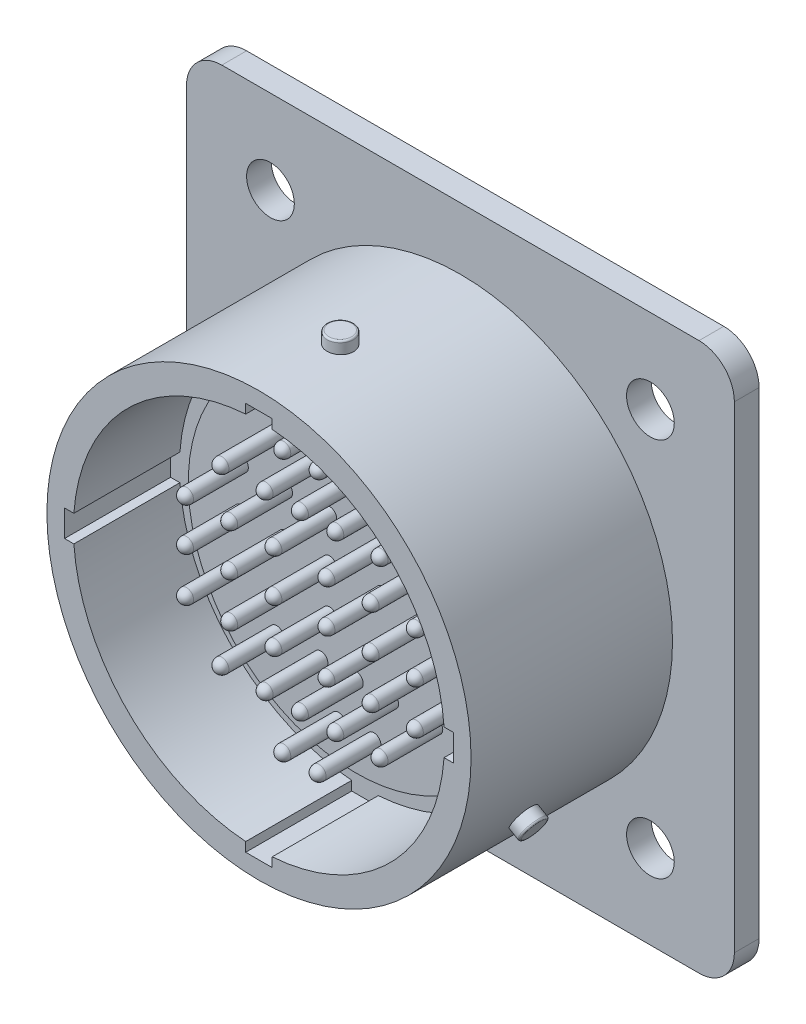
SolidWorks part; units mm, degrees
ref_plane "Спереди" through (0, 0, 0) normal (0, 0, 1) x (1, 0, 0)
ref_plane "Сверху" through (0, 0, 0) normal (0, 1, 0) x (1, 0, 0)
ref_plane "Справа" through (0, 0, 0) normal (1, 0, 0) x (0, 0, -1)
sketch "Эскиз1" plane through (0, 0, 0) normal (0, 0, 1) x (1, 0, 0)
  line L1 (-15.5, 15.5) -> (15.5, 15.5)
  line L2 (-15.5, 15.5) -> (-15.5, -15.5)
  line L3 (-15.5, -15.5) -> (15.5, -15.5)
  line L4 (15.5, 15.5) -> (15.5, -15.5)
  line L5 (0, -15.5) -> (0, 15.5) construction
  line L6 (-15.5, 0) -> (15.5, 0) construction
  point P0 (0, 0)
  dimension "D1" = 31
  dimension "D2" = 31
extrude "Бобышка-Вытянуть1" add sketch "Эскиз1" along normal mid plane 1.4
sketch "Эскиз2" plane through (0, 0, 0.7) normal (0, 0, 1) x (1, 0, 0)
  line L1 (-10.75, 10.75) -> (10.75, 10.75) construction
  line L2 (-10.75, 10.75) -> (-10.75, -10.75) construction
  line L3 (-10.75, -10.75) -> (10.75, -10.75) construction
  line L4 (10.75, 10.75) -> (10.75, -10.75) construction
  line L5 (0, -10.75) -> (0, 10.75) construction
  line L6 (-10.75, 0) -> (10.75, 0) construction
  circle A0 centre (-10.75, 10.75) radius 1.35
  circle A1 centre (10.75, 10.75) radius 1.35
  circle A2 centre (10.75, -10.75) radius 1.35
  circle A3 centre (-10.75, -10.75) radius 1.35
  point P0 (0, 0)
  dimension "D3" = 2.7
  dimension "D1" = 21.5
  dimension "D2" = 21.5
extrude "Вырез-Вытянуть1" cut sketch "Эскиз2" against normal blind 3.4
sketch "Эскиз4" plane through (0, 0, -0.7) normal (0, 0, -1) x (-1, 0, 0)
  circle A0 centre (0, 0) radius 11
  dimension "D1" = 22
extrude "Бобышка-Вытянуть2" add sketch "Эскиз4" along normal blind 1.6
sketch "Эскиз5" plane through (0, 0, 0.7) normal (0, 0, 1) x (1, 0, 0)
  circle A0 centre (0, 0) radius 12
  dimension "D1" = 24
extrude "Бобышка-Вытянуть3" add sketch "Эскиз5" along normal blind 11.4
sketch "Эскиз6" plane through (0, 0, -2.3) normal (0, 0, -1) x (-1, 0, 0)
  circle A2 centre (0, 0) radius 10
  circle A3 centre (0, 0) radius 10
  dimension "D1" = 1
fillet "Скругление1" radius 2 4 edges at (-15.5, -15.5, 0) (15.5, -15.5, 0) (-15.5, 15.5, 0) (15.5, 15.5, 0)
sketch "Эскиз11" plane through (0, 0, 12.1) normal (0, 0, 1) x (1, 0, 0)
  line L0 (0, 7.0707) -> (0, -7.5997) construction
  line L1 (-7.9185, 0) -> (8.5925, 0) construction
  line L2 (-0.75, 11) -> (0.75, 11)
  line L3 (-0.75, 11) -> (-0.75, 10.4732)
  line L4 (0.75, 11) -> (0.75, 10.4732)
  line L5 (11, 0.75) -> (10.4732, 0.75)
  line L6 (11, 0.75) -> (11, -0.75)
  line L7 (11, -0.75) -> (10.4732, -0.75)
  line L8 (0.75, -11) -> (0.75, -10.4732)
  line L9 (0.75, -11) -> (-0.75, -11)
  line L10 (-0.75, -11) -> (-0.75, -10.4732)
  line L11 (-11, -0.75) -> (-10.4732, -0.75)
  line L12 (-11, -0.75) -> (-11, 0.75)
  line L13 (-11, 0.75) -> (-10.4732, 0.75)
  arc A1 (-10.4732, -0.75) -> (-0.75, -10.4732) centre (0, 0) ccw
  circle A2 centre (0, 0) radius 10.5
  arc A3 (-0.75, 10.4732) -> (-10.4732, 0.75) centre (0, 0) ccw
  arc A4 (0.75, -10.4732) -> (10.4732, -0.75) centre (0, 0) ccw
  arc A5 (10.4732, 0.75) -> (0.75, 10.4732) centre (0, 0) ccw
  point P10 (0, 10.5)
  point P11 (0, 11)
  point P28 (0, 0)
  dimension "D2" = 0.5
  dimension "D3" = 1.5
  dimension "D1" = 1.5
  dimension "D4" = 4
extrude "Вырез-Вытянуть5" cut sketch "Эскиз11" against normal blind 6
sketch "Эскиз12" plane through (0, 0, 6.1) normal (0, 0, 1) x (1, 0, 0)
  circle A0 centre (0, 0) radius 9.5
  dimension "D1" = 19
extrude "Бобышка-Вытянуть5" add sketch "Эскиз12" along normal blind 0.5
sketch "Эскиз13" plane through (0, 0, 6.6) normal (0, 0, 1) x (1, 0, 0)
  line L0 (-6.7045, 0) -> (6.9732, 0) construction
  line L1 (0, 4.9143) -> (0, -4.8929) construction
  line L2 (-6.3605, 4.9143) -> (7.9732, 4.9143) construction
  line L3 (-6.3605, 7.4143) -> (7.9732, 7.4143) construction
  circle A4 centre (-1.5, 0) radius 0.4
  circle A6 centre (-4, 0) radius 0.4
  circle A7 centre (-6.5, 0) radius 0.4
  circle A8 centre (-1.5, -2.5) radius 0.4
  circle A9 centre (-4, -2.5) radius 0.4
  circle A10 centre (-6.5, -2.5) radius 0.4
  circle A11 centre (-4, 2.4143) radius 0.4
  circle A12 centre (-6.5, 2.4143) radius 0.4
  circle A13 centre (-1.5, 2.4143) radius 0.4
  circle A14 centre (0, 4.9143) radius 0.4
  circle A15 centre (-2, 4.9143) radius 0.4
  circle A16 centre (-4.5, 4.9143) radius 0.4
  circle A17 centre (-1, 7.4143) radius 0.4
  circle A18 centre (-2, -4.9143) radius 0.4
  circle A19 centre (-1, -7.4143) radius 0.4
  circle A20 centre (0, -4.9143) radius 0.4
  circle A21 centre (-4.5, -4.9143) radius 0.4
  circle A22 centre (4.5, -4.9143) radius 0.4
  circle A23 centre (1, -7.4143) radius 0.4
  circle A24 centre (2, -4.9143) radius 0.4
  circle A25 centre (1, 7.4143) radius 0.4
  circle A26 centre (4.5, 4.9143) radius 0.4
  circle A27 centre (2, 4.9143) radius 0.4
  circle A28 centre (1.5, 2.4143) radius 0.4
  circle A29 centre (6.5, 2.4143) radius 0.4
  circle A30 centre (4, 2.4143) radius 0.4
  circle A31 centre (6.5, -2.5) radius 0.4
  circle A32 centre (4, -2.5) radius 0.4
  circle A33 centre (1.5, -2.5) radius 0.4
  circle A34 centre (6.5, 0) radius 0.4
  circle A35 centre (4, 0) radius 0.4
  circle A36 centre (1.5, 0) radius 0.4
  dimension "D1" = 0.8
  dimension "D2" = 1.5
  dimension "D3" = 2.5
  dimension "D4" = 2.5
  dimension "D8" = 2
  dimension "D9" = 2.5
  dimension "D11" = 1
  dimension "D7" = 2.5
  dimension "D10" = 2.5
  dimension "D5" = 2
  dimension "D6" = 2
extrude "Бобышка-Вытянуть6" add sketch "Эскиз13" along normal blind 3.5
ref_plane "Плоскость1" through (0, 0, 7.5) normal (0, 0, 1) x (1, 0, 0)
sketch "Эскиз14" plane through (0, 0, 7.5) normal (0, 0, 1) x (1, 0, 0)
  line L0 (0, 12.8264) -> (0, 9.1156) construction
  line L1 (0, 12.6686) -> (0.65, 12.6686)
  line L2 (0, 12.6686) -> (0, 11.8686)
  line L3 (0, 11.8686) -> (0.75, 11.8686)
  line L4 (0.75, 11.8686) -> (0.75, 12.5686)
  arc A0 (0.75, 12.5686) -> (0.65, 12.6686) centre (0.65, 12.5686) ccw
  point P5 (0, 12.7094)
  dimension "D3" = 0.1
  dimension "D1" = 0.75
  dimension "D2" = 0.8
revolve "Повернуть1" add sketch "Эскиз14" angle 360 about L0
pattern_circular "Круговой массив1" count 3 over 360 about axis through (0, 0, 0) along (0, 0, 1) of "Повернуть1"
fillet "Скругление2" radius 0.4 32 edges at (6.1, 0, 10.1) (-1.4, -7.4143, 10.1) (1.4, -7.4143, 10.1) (4.9, -4.9143, 10.1) (2.4, -4.9143, 10.1) (-0.4, -4.9143, 10.1) (-2.4, -4.9143, 10.1) (-4.9, -4.9143, 10.1) (6.1, -2.5, 10.1) (6.1, 2.4143, 10.1) (3.6, 2.4143, 10.1) (3.6, -2.5, 10.1) (3.6, 0, 10.1) (1.1, 0, 10.1) (-1.1, 0, 10.1) (1.1, -2.5, 10.1) (-1.1, -2.5, 10.1) (-3.6, -2.5, 10.1) (-6.1, -2.5, 10.1) (-6.1, 0, 10.1) (-3.6, 0, 10.1) (-1.1, 2.4143, 10.1) (1.1, 2.4143, 10.1) (4.1, 4.9143, 10.1) (1.6, 4.9143, 10.1) (0.6, 7.4143, 10.1) (-0.6, 7.4143, 10.1) (0.4, 4.9143, 10.1) (-1.6, 4.9143, 10.1) (-4.1, 4.9143, 10.1) (-3.6, 2.4143, 10.1) (-6.1, 2.4143, 10.1)
extrude "Вырез-Вытянуть6" cut sketch "Эскиз6" against normal up to surface (1.6 mm away) contours A3 up to face at (11, 0, -0.7)
sketch "Эскиз15" plane through (0, 0, -0.7) normal (0, 0, -1) x (-1, 0, 0)
  circle A0 centre (1, 7.4143) radius 0.4
  circle A1 centre (-1, 7.4143) radius 0.4
  circle A2 centre (4.5, 4.9143) radius 0.4
  circle A3 centre (2, 4.9143) radius 0.4
  circle A4 centre (0, 4.9143) radius 0.4
  circle A5 centre (6.5, 2.4143) radius 0.4
  circle A6 centre (4, 2.4143) radius 0.4
  circle A7 centre (1.5, 2.4143) radius 0.4
  circle A8 centre (-1.5, 2.4143) radius 0.4
  circle A9 centre (-4, 2.4143) radius 0.4
  circle A10 centre (-6.5, 2.4143) radius 0.4
  circle A11 centre (-4.5, 4.9143) radius 0.4
  circle A12 centre (-2, 4.9143) radius 0.4
  circle A13 centre (6.5, 0) radius 0.4
  circle A14 centre (4, 0) radius 0.4
  circle A15 centre (1.5, 0) radius 0.4
  circle A16 centre (-1.5, 0) radius 0.4
  circle A17 centre (-4, 0) radius 0.4
  circle A18 centre (-6.5, 0) radius 0.4
  circle A19 centre (6.5, -2.5) radius 0.4
  circle A20 centre (4, -2.5) radius 0.4
  circle A21 centre (1.5, -2.5) radius 0.4
  circle A22 centre (-1.5, -2.5) radius 0.4
  circle A23 centre (-4, -2.5) radius 0.4
  circle A24 centre (-6.5, -2.5) radius 0.4
  circle A25 centre (-4.5, -4.9143) radius 0.4
  circle A26 centre (-2, -4.9143) radius 0.4
  circle A27 centre (0, -4.9143) radius 0.4
  circle A28 centre (2, -4.9143) radius 0.4
  circle A29 centre (4.5, -4.9143) radius 0.4
  circle A30 centre (1, -7.4143) radius 0.4
  circle A31 centre (-1, -7.4143) radius 0.4
  dimension "D1" = 0.8
extrude "Бобышка-Вытянуть7" add sketch "Эскиз15" along normal blind 3.6
sketch "Эскиз16" plane through (0, 0, 0) normal (1, 0, 0) x (0, 0, -1)
  line L0 (4.3, 7.8143) -> (2.8, 7.8143)
  line L1 (4.3, 7.8143) -> (0.7, 7.8143) construction
  line L2 (4.3, 7.0143) -> (4.3, 7.8143) construction
  line L3 (4.3, 7.8143) -> (4.3, 7.4143)
  line L4 (4.3, 5.3143) -> (4.3, 4.9143)
  line L5 (4.3, 5.3143) -> (2.8, 5.3143)
  line L6 (4.3, 2.8143) -> (4.3, 2.4143)
  line L7 (4.3, 0.4) -> (4.3, 0)
  line L8 (4.3, 2.8143) -> (2.8, 2.8143)
  line L9 (4.3, 0.4) -> (2.8, 0.4)
  line L10 (4.3, 2.8143) -> (0.7, 2.8143) construction
  line L11 (4.3, -2.1) -> (4.3, -2.5)
  line L12 (4.3, -2.1) -> (2.8, -2.1)
  line L13 (4.3, -4.5143) -> (2.8, -4.5143)
  line L14 (4.3, -4.5143) -> (4.3, -4.9143)
  line L15 (4.3, -7.0143) -> (4.3, -7.4143)
  line L16 (4.3, -7.0143) -> (2.8, -7.0143)
  line L17 (4.3, 2.0143) -> (4.3, 2.8143) construction
  arc A0 (2.8, 7.8143) -> (4.3, 7.4143) centre (4.2967, 10.4143) ccw
  arc A1 (2.8, 5.3143) -> (4.3, 4.9143) centre (4.2967, 7.9143) ccw
  arc A2 (2.8, 2.8143) -> (4.3, 2.4143) centre (4.2967, 5.4143) ccw
  arc A3 (2.8, 0.4) -> (4.3, 0) centre (4.2967, 3) ccw
  arc A4 (2.8, -2.1) -> (4.3, -2.5) centre (4.2967, 0.5) ccw
  arc A5 (2.8, -4.5143) -> (4.3, -4.9143) centre (4.2967, -1.9143) ccw
  arc A6 (2.8, -7.0143) -> (4.3, -7.4143) centre (4.2967, -4.4143) ccw
  point P36 (0, 0)
  point P37 (4.3, 2.4143)
  dimension "D2" = 3
  dimension "D4" = 3
  dimension "D1" = 1.5
  dimension "D3" = 1.5
extrude "Вырез-Вытянуть7" cut sketch "Эскиз16" against normal mid plane 22
sketch "Эскиз17" plane through (0, 0, -4.3) normal (0, 0, -1) x (-1, 0, 0)
  line L0 (-1.4, 7.4143) -> (-0.6, 7.4143) construction
  line L1 (1.4, 7.4143) -> (0.6, 7.4143) construction
  line L2 (-4.1, 4.9143) -> (-4.9, 4.9143) construction
  line L3 (-2.4, 4.9143) -> (-1.6, 4.9143) construction
  line L4 (0.4, 4.9143) -> (-0.4, 4.9143) construction
  line L5 (2.4, 4.9143) -> (1.6, 4.9143) construction
  line L6 (4.9, 4.9143) -> (4.1, 4.9143) construction
  line L7 (-6.9, 0) -> (-6.1, 0) construction
  line L8 (-3.6, 0) -> (-4.4, 0) construction
  line L9 (-1.1, 0) -> (-1.9, 0) construction
  line L10 (1.9, 0) -> (1.1, 0) construction
  line L11 (4.4, 0) -> (3.6, 0) construction
  line L12 (6.9, 0) -> (6.1, 0) construction
  line L13 (-6.9, -2.5) -> (-6.1, -2.5) construction
  line L14 (-3.6, -2.5) -> (-4.4, -2.5) construction
  line L15 (-1.1, -2.5) -> (-1.9, -2.5) construction
  line L16 (-1.6, -4.9143) -> (-2.4, -4.9143) construction
  line L17 (0.4, -4.9143) -> (-0.4, -4.9143) construction
  line L18 (-1.4, -7.4143) -> (-0.6, -7.4143) construction
  line L19 (2.4, -4.9143) -> (1.6, -4.9143) construction
  line L20 (4.1, -4.9143) -> (4.9, -4.9143) construction
  line L21 (1.9, -2.5) -> (1.1, -2.5) construction
  line L22 (4.4, -2.5) -> (3.6, -2.5) construction
  line L23 (-6.9, 2.4143) -> (-6.1, 2.4143) construction
  line L24 (-3.6, 2.4143) -> (-4.4, 2.4143) construction
  line L25 (-1.1, 2.4143) -> (-1.9, 2.4143) construction
  line L26 (1.9, 2.4143) -> (1.1, 2.4143) construction
  line L27 (4.4, 2.4143) -> (3.6, 2.4143) construction
  line L28 (6.9, 2.4143) -> (6.1, 2.4143) construction
  circle A0 centre (-1, 7.4143) radius 0.325
  circle A1 centre (1, 7.4143) radius 0.325
  circle A2 centre (-4.5, 4.9143) radius 0.325
  circle A3 centre (-2, 4.9143) radius 0.325
  circle A4 centre (0, 4.9143) radius 0.325
  circle A5 centre (2, 4.9143) radius 0.325
  circle A6 centre (4.5, 4.9143) radius 0.325
  circle A7 centre (-6.5, 0) radius 0.325
  circle A8 centre (-4, 0) radius 0.325
  circle A9 centre (-1.5, 0) radius 0.325
  circle A10 centre (1.5, 0) radius 0.325
  circle A11 centre (4, 0) radius 0.325
  circle A12 centre (6.5, 0) radius 0.325
  circle A13 centre (-6.5, -2.5) radius 0.325
  circle A14 centre (-4, -2.5) radius 0.325
  circle A15 centre (-1.5, -2.5) radius 0.325
  circle A16 centre (-4.5, -4.9143) radius 0.325
  circle A17 centre (-2, -4.9143) radius 0.325
  circle A18 centre (0, -4.9143) radius 0.325
  circle A19 centre (-1, -7.4143) radius 0.325
  circle A20 centre (1, -7.4143) radius 0.325
  circle A21 centre (2, -4.9143) radius 0.325
  circle A22 centre (4.5, -4.9143) radius 0.325
  circle A23 centre (1.5, -2.5) radius 0.325
  circle A24 centre (4, -2.5) radius 0.325
  circle A25 centre (6.5, -2.5) radius 0.325
  circle A26 centre (-6.5, 2.4143) radius 0.325
  circle A27 centre (-4, 2.4143) radius 0.325
  circle A28 centre (-1.5, 2.4143) radius 0.325
  circle A29 centre (1.5, 2.4143) radius 0.325
  circle A30 centre (4, 2.4143) radius 0.325
  circle A31 centre (6.5, 2.4143) radius 0.325
  point P6 (1, 7.4143)
  point P11 (-4.5, 4.9143)
  point P16 (-2, 4.9143)
  point P21 (0, 4.9143)
  point P26 (2, 4.9143)
  point P31 (4.5, 4.9143)
  point P36 (-6.5, 0)
  point P41 (-4, 0)
  point P46 (-1.5, 0)
  point P51 (1.5, 0)
  point P56 (4, 0)
  point P61 (6.5, 0)
  point P66 (-6.5, -2.5)
  point P71 (-4, -2.5)
  point P76 (-1.5, -2.5)
  point P81 (-4.5, -4.9143)
  point P85 (-2, -4.9143)
  point P90 (0, -4.9143)
  point P95 (-1, -7.4143)
  point P100 (1, -7.4143)
  point P104 (2, -4.9143)
  point P109 (4.5, -4.9143)
  point P114 (1.5, -2.5)
  point P119 (4, -2.5)
  point P124 (6.5, -2.5)
  point P128 (-6.5, 2.4143)
  point P133 (-4, 2.4143)
  point P138 (-1.5, 2.4143)
  point P143 (1.5, 2.4143)
  point P148 (4, 2.4143)
  point P153 (6.5, 2.4143)
  dimension "D1" = 0.65
extrude "Вырез-Вытянуть8" cut sketch "Эскиз17" against normal blind 3
